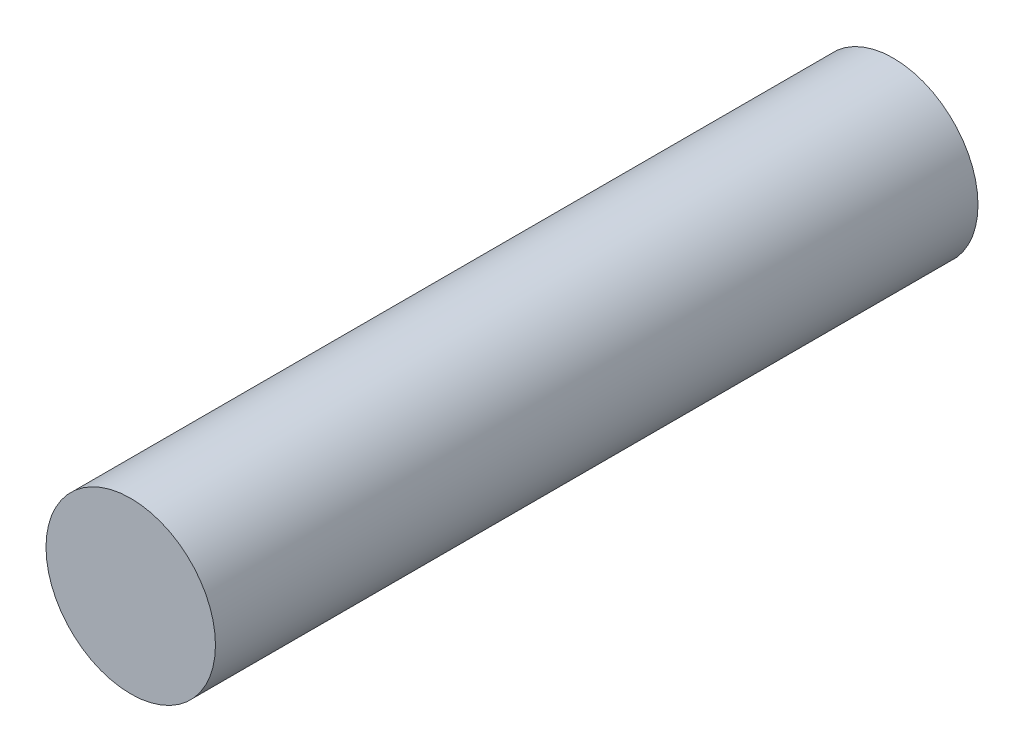
SolidWorks part; units mm, degrees
ref_plane "Front Plane" through (0, 0, 0) normal (0, 0, 1) x (1, 0, 0)
ref_plane "Top Plane" through (0, 0, 0) normal (0, 1, 0) x (1, 0, 0)
ref_plane "Right Plane" through (0, 0, 0) normal (1, 0, 0) x (0, 0, -1)
sketch "Sketch1" plane through (0, 0, 0) normal (0, 0, 1) x (1, 0, 0)
  circle A0 centre (0, 0) radius 12.7
  dimension "D1" = 25.4
extrude "Boss-Extrude1" add sketch "Sketch1" along normal blind 114.3 contours A0
